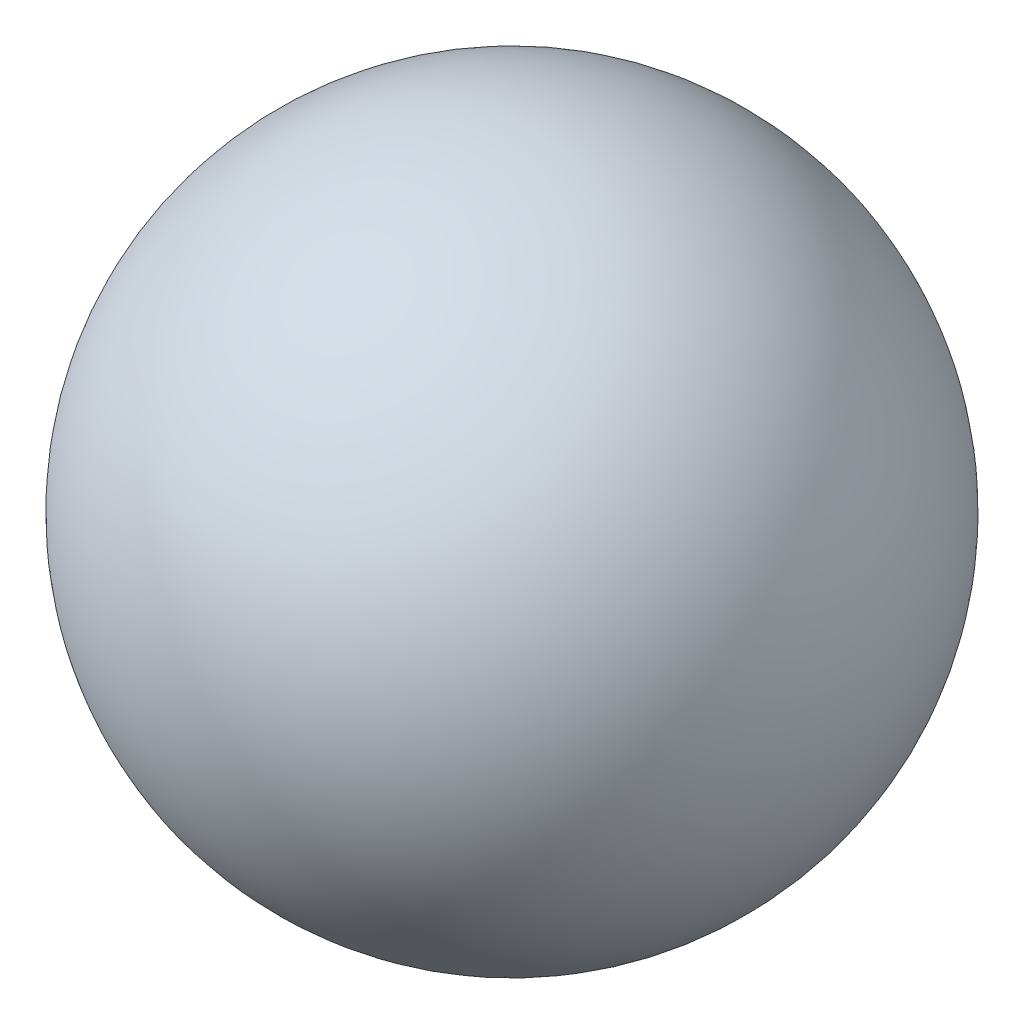
SolidWorks part; units mm, degrees
ref_plane "Front Plane" through (0, 0, 0) normal (0, 0, 1) x (1, 0, 0)
ref_plane "Top Plane" through (0, 0, 0) normal (0, 1, 0) x (1, 0, 0)
ref_plane "Right Plane" through (0, 0, 0) normal (1, 0, 0) x (0, 0, -1)
sketch "Sketch1" plane through (0, 0, 0) normal (0, 1, 0) x (1, 0, 0)
  line L0 (0, 36.83) -> (0, -36.83)
  arc A0 (0, -36.83) -> (0, 36.83) centre (0, 0) ccw
  dimension "D1" = 73.66
revolve "Revolve1" add sketch "Sketch1" angle 360 about L0
